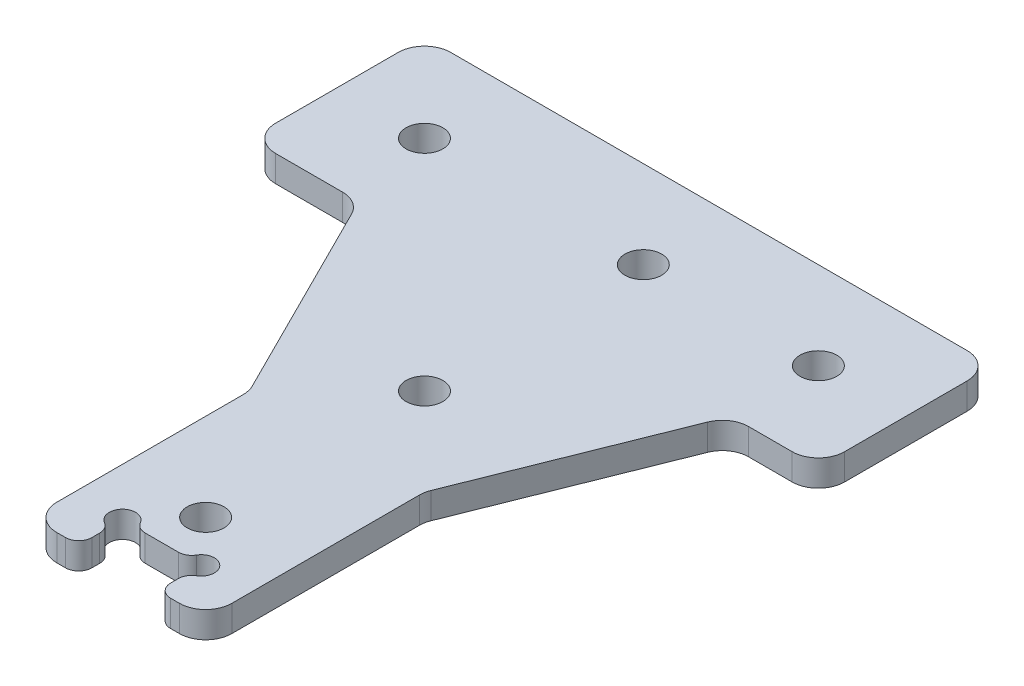
SolidWorks part; units mm, degrees
material "A-玻璃纤维"
ref_plane "前视基准面" through (0, 0, 0) normal (0, 0, 1) x (1, 0, 0)
ref_plane "上视基准面" through (0, 0, 0) normal (0, 1, 0) x (1, 0, 0)
ref_plane "右视基准面" through (0, 0, 0) normal (1, 0, 0) x (0, 0, -1)
sketch "草图1" plane through (0, 0, 0) normal (0, 1, 0) x (1, 0, 0)
  line L0 (-43.2884, 0) -> (46.6978, 0) construction
  line L1 (0, 0) -> (0, -50) construction
  line L2 (30, 10) -> (-35, 10)
  line L3 (-35, 10) -> (-35, -10)
  line L4 (-35, -10) -> (-10, -10)
  line L5 (-10, -10) -> (-10, -60)
  line L6 (-10, -60) -> (10, -60)
  line L7 (10, -60) -> (10, -10)
  line L8 (10, -10) -> (30, -10)
  line L9 (30, -10) -> (30, 10)
  line L10 (-22.5, -10) -> (-10, -35)
  line L11 (20, -10) -> (10, -35)
  circle A0 centre (0, 0) radius 2.1
  circle A1 centre (20, 0) radius 2.1
  circle A2 centre (-25, 0) radius 2.1
  circle A3 centre (0, -25) radius 2.1
  circle A4 centre (0, -50) radius 2.1
  dimension "D1" = 4.2
  dimension "D2" = 20
  dimension "D3" = 25
  dimension "D4" = 25
  dimension "D5" = 25
  dimension "D7" = 10
  dimension "D6" = 20
  dimension "D8" = 10
  dimension "D9" = 20
  dimension "D10" = 10
extrude "凸台-拉伸1" add sketch "草图1" along normal blind 3 contours L8 L9 L2 L3 L4 L5 L6 L7 A4 A3 A2 A1 A0 | L4 L10 L5 | L11 L8 L7
fillet "圆角1" radius 3 10 edges at (10, 1.5, 35) (10, 1.5, 60) (-10, 1.5, 60) (-10, 1.5, 35) (-22.5, 1.5, 10) (-35, 1.5, 10) (30, 1.5, -10) (30, 1.5, 10) (20, 1.5, 10) (-35, 1.5, -10)
sketch "草图2" plane through (0, 3, 0) normal (0, 1, 0) x (1, 0, 0)
  line L0 (-7, -60) -> (7, -60) construction
  line L1 (-4.5, -60) -> (4.5, -60)
  line L2 (-4.5, -60) -> (-4.5, -55)
  line L3 (-4.5, -55) -> (4.5, -55)
  line L4 (4.5, -60) -> (4.5, -55)
  line L5 (0, -55) -> (0, -60) construction
  line L6 (-4.5, -57.5) -> (4.5, -57.5) construction
  circle A0 centre (0, -50) radius 2.1 construction
  point P80 (0, -57.5)
  dimension "D1" = 9
  dimension "D2" = 5
extrude "切除-拉伸1" cut sketch "草图2" against normal blind 3
sketch "草图3" plane through (0, 3, 0) normal (0, 1, 0) x (1, 0, 0)
  circle A0 centre (-4.5, -55) radius 1.5
  circle A1 centre (4.5, -55) radius 1.5
  dimension "D1" = 3
extrude "切除-拉伸2" cut sketch "草图3" against normal blind 10
fillet "圆角2" radius 1.5 6 edges at (3, 1.5, 55) (4.5, 1.5, 56.5) (4.5, 1.5, 60) (-4.5, 1.5, 56.5) (-3, 1.5, 55) (-4.5, 1.5, 60)
